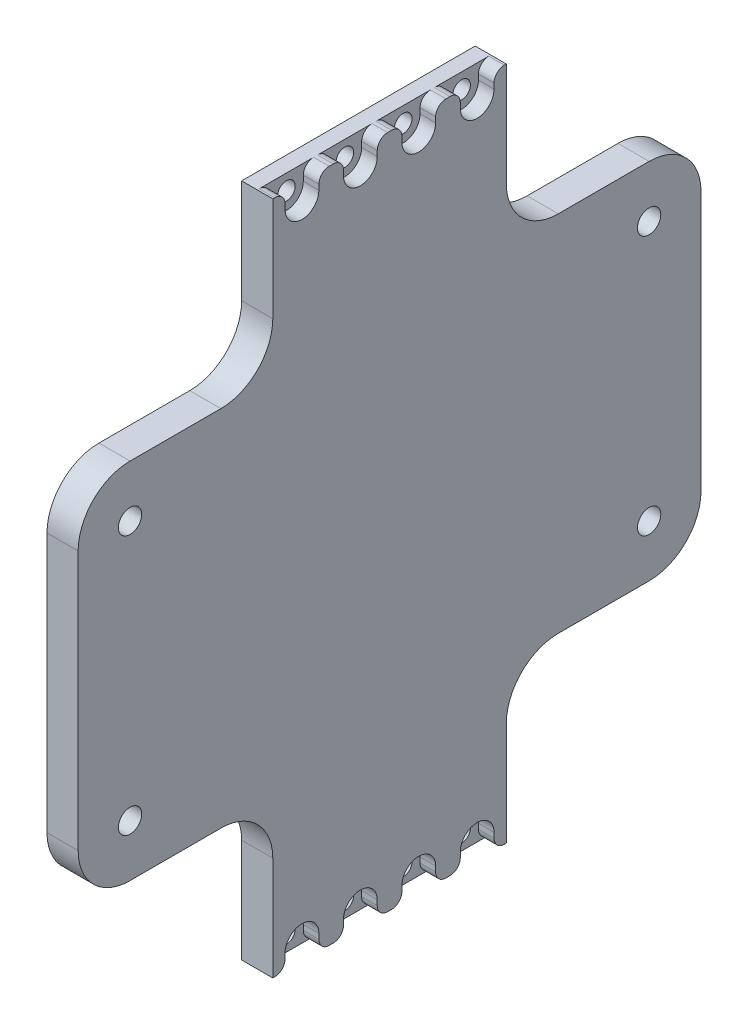
SolidWorks part; units mm, degrees
material "Сплав 2024"
ref_plane "Спереди" through (0, 0, 0) normal (0, 0, 1) x (1, 0, 0)
ref_plane "Сверху" through (0, 0, 0) normal (0, 1, 0) x (1, 0, 0)
ref_plane "Справа" through (0, 0, 0) normal (1, 0, 0) x (0, 0, -1)
sketch "Эскиз1" plane through (0, 0, 0) normal (0, 1, 0) x (1, 0, 0)
  line L1 (0, 0) -> (6, 0)
  line L2 (0, 0) -> (0, -30)
  line L3 (0, -30) -> (6, -30)
  line L4 (6, 0) -> (6, -30)
  dimension "D1" = 6
  dimension "D2" = 30
extrude "Бобышка-Вытянуть1" add sketch "Эскиз1" along normal blind 130
sketch "Эскиз8" plane through (6, 0, 0) normal (1, 0, 0) x (0, 0, -1)
  line L0 (-15, 130) -> (-15, 0) construction
  line L1 (-30, 130) -> (0, 130) construction
  line L2 (-30, 0) -> (0, 0) construction
  line L3 (19.447, 65) -> (-49.447, 65) construction
  line L4 (0, 130) -> (0, 0) construction
  line L5 (-26, 106) -> (-4, 106) construction
  line L6 (-26, 106) -> (-26, 24) construction
  line L7 (-26, 24) -> (-4, 24) construction
  line L8 (-4, 106) -> (-4, 24) construction
  line L9 (-26, 106) -> (-4, 24) construction
  line L10 (-26, 24) -> (-4, 106) construction
  point P8 (-15, 65)
  point P9 (-15, 65)
  dimension "D1" = 4
  dimension "D2" = 82
sketch "Эскиз11" plane through (6, 0, 0) normal (1, 0, 0) x (0, 0, -1)
  line L0 (-15, 130) -> (-15, 0) construction
  line L1 (-30, 130) -> (0, 130) construction
  line L2 (-30, 0) -> (0, 0) construction
  line L3 (-37.5, 124) -> (-37.5, 100)
  line L4 (-37.5, 124) -> (7.5, 124) construction
  line L5 (-37.5, 124) -> (-37.5, 130)
  line L6 (-37.5, 130) -> (7.5, 130)
  line L7 (7.5, 124) -> (7.5, 130)
  line L8 (-37.5, 124) -> (7.5, 130) construction
  line L9 (-37.5, 130) -> (7.5, 124) construction
  line L10 (7.5, 100) -> (45, 100)
  line L11 (7.5, 124) -> (7.5, 100)
  line L12 (-37.5, 30) -> (-37.5, 6)
  line L13 (7.5, 30) -> (45, 30)
  line L14 (-37.5, 127) -> (7.5, 127) construction
  line L15 (-31.875, 130) -> (-31.875, 124) construction
  line L16 (-26.25, 130) -> (-26.25, 124) construction
  line L17 (-20.625, 130) -> (-20.625, 124) construction
  line L18 (-15, 130) -> (-15, 124) construction
  line L19 (-15, 65) -> (-5.455, 65) construction
  line L20 (-15, 0) -> (-15, 6) construction
  line L21 (-20.625, 0) -> (-20.625, 6) construction
  line L22 (-26.25, 0) -> (-26.25, 6) construction
  line L23 (-31.875, 0) -> (-31.875, 6) construction
  line L24 (-37.5, 3) -> (7.5, 3) construction
  line L25 (-37.5, 0) -> (7.5, 6) construction
  line L26 (-37.5, 6) -> (7.5, 0) construction
  line L27 (-37.5, 6) -> (7.5, 6) construction
  line L28 (-75, 100) -> (-37.5, 100)
  line L29 (-75, 100) -> (-75, 30)
  line L30 (7.5, 6) -> (7.5, 0)
  line L31 (-37.5, 0) -> (7.5, 0)
  line L32 (-37.5, 6) -> (-37.5, 0)
  line L33 (-75, 30) -> (-37.5, 30)
  line L34 (-9.375, 130) -> (-9.375, 124) construction
  line L35 (-3.75, 130) -> (-3.75, 124) construction
  line L36 (1.875, 130) -> (1.875, 124) construction
  line L37 (-9.375, 0) -> (-9.375, 6) construction
  line L38 (-3.75, 0) -> (-3.75, 6) construction
  line L39 (1.875, 0) -> (1.875, 6) construction
  line L40 (45, 100) -> (45, 30)
  line L41 (-75, 100) -> (45, 30) construction
  line L42 (-75, 30) -> (45, 100) construction
  line L43 (7.5, 30) -> (7.5, 6)
  point P6 (-15, 127)
  point P45 (-15, 3)
  dimension "D1" = 6
  dimension "D2" = 45
  dimension "D3" = 70
  dimension "D4" = 5.625
  dimension "D5" = 5.625
  dimension "D6" = 5.625
  dimension "D7" = 5.625
  dimension "D8" = 5.625
  dimension "D9" = 5.625
  dimension "D10" = 5.625
  dimension "D11" = 120
extrude "Бобышка-Вытянуть3" add sketch "Эскиз11" against normal up to surface (6 mm away) up to face at (0, 65, 15)
hole_wizard "Цековка для винта с внутренним шестигранником M31" positions "Эскиз13" profile "Эскиз12" counterbore size "M3" standard "Ansi Metric" end condition through all
sketch "Эскиз13" plane through (6, 0, 0) normal (1, 0, 0) x (0, 0, -1)
  line L0 (-31.875, 130) -> (-31.875, 124) construction
  line L4 (-31.875, 0) -> (-31.875, 6) construction
  line L8 (1.875, 130) -> (1.875, 124) construction
  line L9 (-9.375, 130) -> (-9.375, 124) construction
  line L10 (-20.625, 130) -> (-20.625, 124) construction
  line L11 (1.875, 0) -> (1.875, 6) construction
  line L12 (-9.375, 0) -> (-9.375, 6) construction
  line L13 (-20.625, 0) -> (-20.625, 6) construction
  point P0 (-31.875, 127)
  point P4 (-20.625, 127)
  point P8 (-9.375, 127)
  point P12 (1.875, 127)
  point P16 (-31.875, 3)
  point P20 (-20.625, 3)
  point P24 (-9.375, 3)
  point P28 (1.875, 3)
sketch "Эскиз12" plane through (6, 127, 31.875) normal (0, 1, 0) x (0, 0, -1)
  line L0 (0, 0) -> (0, 6)
  line L1 (0, 6) -> (1.7, 6)
  line L3 (1.7, 6) -> (1.7, 3)
  line L4 (1.7, 3) -> (3.25, 3)
  line L5 (3.25, 3) -> (3.25, 0)
  line L7 (3.25, 0) -> (0, 0)
  line L11 (0, -6.35) -> (0, 107.95) construction
  dimension "Диаметр сквозного отверстия" = 3.4
  dimension "Глубина сквозного отверстия" = 6
  dimension "Диаметр цековки" = 6.5
  dimension "Глубина цековки" = 3
sketch "Эскиз14" plane through (6, 0, 0) normal (1, 0, 0) x (0, 0, -1)
  line L0 (-75, 65) -> (45, 65) construction
  line L1 (-75, 100) -> (-75, 30) construction
  line L2 (45, 30) -> (45, 100) construction
  line L3 (-15, 130) -> (-15, 0) construction
  line L4 (-19.375, 130) -> (-10.625, 130) construction
  line L5 (-19.375, 0) -> (-10.625, 0) construction
  line L6 (-65, 100) -> (-65, 30) construction
  line L7 (-37.5, 100) -> (-75, 100) construction
  line L8 (-75, 30) -> (-37.5, 30) construction
  line L9 (35, 100) -> (35, 30) construction
  line L10 (45, 100) -> (7.5, 100) construction
  line L11 (7.5, 30) -> (45, 30) construction
  line L12 (-75, 90) -> (45, 90) construction
  line L13 (-75, 40) -> (45, 40) construction
  dimension "D1" = 10
  dimension "D2" = 10
  dimension "D3" = 10
  dimension "D4" = 10
hole_wizard "Отверстие с зазором M41" positions "Эскиз16" profile "Эскиз15" hole size "M4" standard "Ansi Metric" end condition through all
sketch "Эскиз16" plane through (6, 0, 0) normal (1, 0, 0) x (0, 0, -1)
  line L0 (-75, 90) -> (45, 90) construction
  line L1 (-75, 40) -> (45, 40) construction
  line L2 (35, 100) -> (35, 30) construction
  line L3 (-65, 100) -> (-65, 30) construction
  point P0 (-65, 90)
  point P4 (-65, 40)
  point P8 (35, 40)
  point P10 (35, 90)
sketch "Эскиз15" plane through (6, 90, 65) normal (0, 1, 0) x (0, 0, -1)
  line L0 (0, 0) -> (0, 6)
  line L1 (0, 6) -> (2.25, 6)
  line L2 (2.25, 6) -> (2.25, 0)
  line L5 (2.25, 0) -> (0, 0)
  line L11 (0, -6.35) -> (0, 107.95) construction
  dimension "Диаметр сквозного отверстия" = 4.5
  dimension "Глубина сквозного отверстия" = 6
fillet "Скругление1" radius 10 8 edges at (3, 100, -45) (3, 30, -45) (3, 100, 75) (3, 30, 75) (3, 30, 37.5) (3, 30, -7.5) (3, 100, 37.5) (3, 100, -7.5)
sketch "Эскиз17" plane through (6, 0, 0) normal (1, 0, 0) x (0, 0, -1)
  line L0 (-12.625, 127) -> (-6.125, 127)
  line L1 (-1.375, 127) -> (5.125, 127)
  line L2 (-1.375, 127) -> (-1.375, 132)
  line L3 (-1.375, 132) -> (5.125, 132)
  line L4 (5.125, 127) -> (5.125, 132)
  line L5 (-12.625, 127) -> (-12.625, 132)
  line L6 (-12.625, 132) -> (-6.125, 132)
  line L7 (-6.125, 127) -> (-6.125, 132)
  line L8 (-23.875, 127) -> (-17.375, 127)
  line L9 (-23.875, 127) -> (-23.875, 132)
  line L10 (-23.875, 132) -> (-17.375, 132)
  line L11 (-17.375, 127) -> (-17.375, 132)
  line L12 (-35.125, 127) -> (-28.625, 127)
  line L13 (-35.125, 127) -> (-35.125, 132)
  line L14 (-35.125, 132) -> (-28.625, 132)
  line L15 (-28.625, 127) -> (-28.625, 132)
  line L16 (-75, 65) -> (45, 65) construction
  line L17 (-75, 90) -> (-75, 40) construction
  line L18 (45, 40) -> (45, 90) construction
  line L19 (-28.625, 3) -> (-28.625, -2)
  line L20 (-35.125, -2) -> (-28.625, -2)
  line L21 (-35.125, 3) -> (-35.125, -2)
  line L22 (-35.125, 3) -> (-28.625, 3)
  line L23 (-17.375, 3) -> (-17.375, -2)
  line L24 (-23.875, -2) -> (-17.375, -2)
  line L25 (-23.875, 3) -> (-23.875, -2)
  line L26 (-23.875, 3) -> (-17.375, 3)
  line L27 (-6.125, 3) -> (-6.125, -2)
  line L28 (-12.625, -2) -> (-6.125, -2)
  line L29 (-12.625, 3) -> (-12.625, -2)
  line L30 (5.125, 3) -> (5.125, -2)
  line L31 (-1.375, -2) -> (5.125, -2)
  line L32 (-1.375, 3) -> (-1.375, -2)
  line L33 (-1.375, 3) -> (5.125, 3)
  line L34 (-12.625, 3) -> (-6.125, 3)
  arc A0 (0.625, 130) -> (3.125, 130) centre (1.875, 127) ccw construction
  arc A1 (0.625, 130) -> (3.125, 130) centre (1.875, 127) ccw construction
  dimension "D1" = 5
  dimension "D2" = 4
extrude "Вырез-Вытянуть1" cut sketch "Эскиз17" against normal up to surface (3 mm away) up to face at (3, 126.875, 31.875)
fillet "Скругление2" radius 2 16 edges at (4.5, 130, 6.125) (4.5, 130, -5.125) (4.5, 130, 1.375) (4.5, 0, 6.125) (4.5, 0, 17.375) (4.5, 0, 28.625) (4.5, 0, 35.125) (4.5, 0, 23.875) (4.5, 0, 12.625) (4.5, 0, 1.375) (4.5, 0, -5.125) (4.5, 130, 35.125) (4.5, 130, 23.875) (4.5, 130, 28.625) (4.5, 130, 17.375) (4.5, 130, 12.625)
sketch "Эскиз18" plane through (0, 0, 0) normal (1, 0, 0) x (0, 0, -1)
  line L0 (-75, 90) -> (-75, 40) construction
  line L1 (-26.625, 0) -> (-37.125, 0) construction
  point P0 (-75, 0)
equation "\"D4@Эскиз11\"=\"D2@Эскиз11\"/8"
equation "\"D5@Эскиз11\"=\"D4@Эскиз11\""
equation "\"D6@Эскиз11\"=\"D4@Эскиз11\""
equation "\"D7@Эскиз11\"=\"D4@Эскиз11\""
equation "\"D8@Эскиз11\"=\"D4@Эскиз11\""
equation "\"D9@Эскиз11\"=\"D4@Эскиз11\""
equation "\"D10@Эскиз11\"=\"D4@Эскиз11\""
